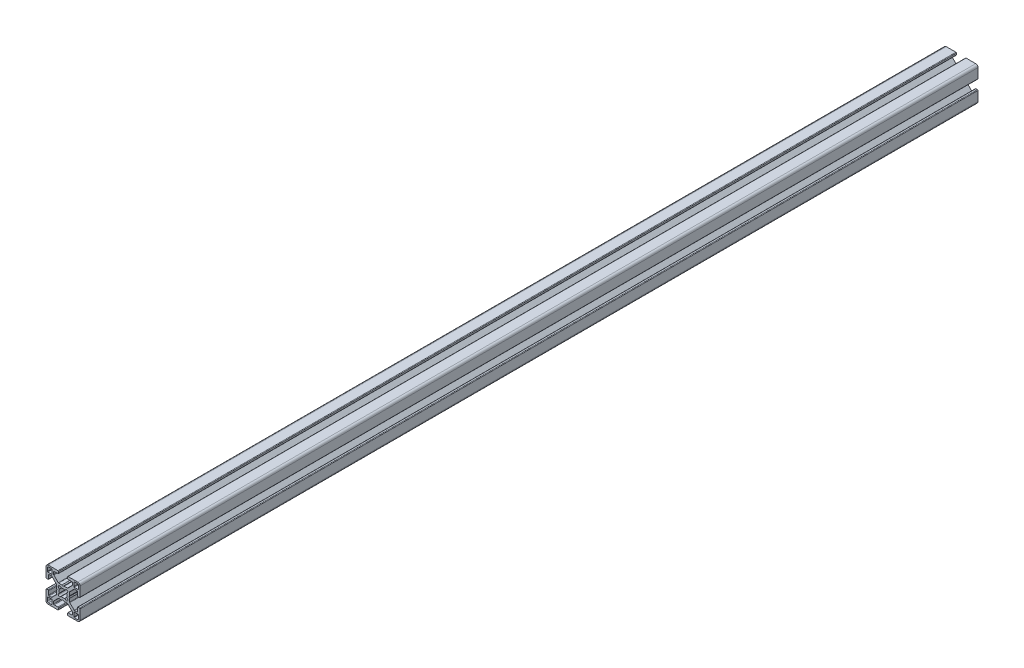
SolidWorks part; units mm, degrees
ref_plane "Plano frontal" through (0, 0, 0) normal (0, 0, 1) x (1, 0, 0)
ref_plane "Plano superior" through (0, 0, 0) normal (0, 1, 0) x (1, 0, 0)
ref_plane "Plano direito" through (0, 0, 0) normal (1, 0, 0) x (0, 0, -1)
ref_plane "Plano1"
sketch "Esboço1" plane through (0, 0, 0) normal (0, 0, 1) x (1, 0, 0)
  line L0 (-13, -15) -> (-4.508, -15)
  line L1 (-4, -14.492) -> (-4, -13.251)
  line L2 (-4.508, -12.743) -> (-7.742, -12.743)
  line L3 (-8.25, -12.235) -> (-8.25, -10.2642)
  line L4 (-8.1012, -9.905) -> (-4.1795, -5.9833)
  line L5 (-3.8203, -5.8345) -> (-0.949, -5.8345)
  line L6 (-0.949, -5.8345) -> (0, -5.325)
  line L7 (0, -5.325) -> (0.949, -5.8345)
  line L8 (0.949, -5.8345) -> (3.8216, -5.8345)
  line L9 (4.1808, -5.9833) -> (8.1012, -9.9037)
  line L10 (8.25, -10.2629) -> (8.25, -12.235)
  line L11 (7.742, -12.743) -> (4.508, -12.743)
  line L12 (4, -13.251) -> (4, -14.492)
  line L13 (4.508, -15) -> (13, -15)
  line L14 (15, -13) -> (15, -4.508)
  line L15 (14.492, -4) -> (13.251, -4)
  line L16 (12.743, -4.508) -> (12.743, -7.742)
  line L17 (12.235, -8.25) -> (10.2642, -8.25)
  line L18 (9.905, -8.1012) -> (5.9833, -4.1795)
  line L19 (5.8345, -3.8203) -> (5.8345, -0.949)
  line L20 (5.8345, -0.949) -> (5.325, 0)
  line L21 (5.325, 0) -> (5.8345, 0.949)
  line L22 (5.8345, 0.949) -> (5.8345, 3.8216)
  line L23 (5.9833, 4.1808) -> (9.9037, 8.1012)
  line L24 (10.2629, 8.25) -> (12.235, 8.25)
  line L25 (12.743, 7.742) -> (12.743, 4.508)
  line L26 (13.251, 4) -> (14.492, 4)
  line L27 (15, 4.508) -> (15, 13)
  line L28 (13, 15) -> (4.508, 15)
  line L29 (4, 14.492) -> (4, 13.251)
  line L30 (4.508, 12.743) -> (7.742, 12.743)
  line L31 (8.25, 12.235) -> (8.25, 10.2642)
  line L32 (8.1012, 9.905) -> (4.1795, 5.9833)
  line L33 (3.8203, 5.8345) -> (0.949, 5.8345)
  line L34 (0.949, 5.8345) -> (0, 5.325)
  line L35 (0, 5.325) -> (-0.949, 5.8345)
  line L36 (-0.949, 5.8345) -> (-3.8216, 5.8345)
  line L37 (-4.1808, 5.9833) -> (-8.1012, 9.9037)
  line L38 (-8.25, 10.2629) -> (-8.25, 12.235)
  line L39 (-7.742, 12.743) -> (-4.508, 12.743)
  line L40 (-4, 13.251) -> (-4, 14.492)
  line L41 (-4.508, 15) -> (-13, 15)
  line L42 (-15, 13) -> (-15, 4.508)
  line L43 (-14.492, 4) -> (-13.251, 4)
  line L44 (-12.743, 4.508) -> (-12.743, 7.742)
  line L45 (-12.235, 8.25) -> (-10.2642, 8.25)
  line L46 (-9.905, 8.1012) -> (-5.9833, 4.1795)
  line L47 (-5.8345, 3.8203) -> (-5.8345, 0.949)
  line L48 (-5.8345, 0.949) -> (-5.325, 0)
  line L49 (-5.325, 0) -> (-5.8345, -0.949)
  line L50 (-5.8345, -0.949) -> (-5.8345, -3.8216)
  line L51 (-5.9833, -4.1808) -> (-9.9037, -8.1012)
  line L52 (-10.2629, -8.25) -> (-12.235, -8.25)
  line L53 (-12.743, -7.742) -> (-12.743, -4.508)
  line L54 (-13.251, -4) -> (-14.492, -4)
  line L55 (-15, -4.508) -> (-15, -13)
  line L56 (9.5, 13.319) -> (9.5, 9.881)
  line L57 (9.881, 9.5) -> (13.319, 9.5)
  line L58 (13.7, 9.881) -> (13.7, 12.7)
  line L59 (12.7, 13.7) -> (9.881, 13.7)
  line L60 (9.5, -9.881) -> (9.5, -13.319)
  line L61 (9.881, -13.7) -> (12.7, -13.7)
  line L62 (13.7, -12.7) -> (13.7, -9.881)
  line L63 (13.319, -9.5) -> (9.881, -9.5)
  line L64 (-13.7, -9.881) -> (-13.7, -12.7)
  line L65 (-12.7, -13.7) -> (-9.881, -13.7)
  line L66 (-9.5, -13.319) -> (-9.5, -9.881)
  line L67 (-9.881, -9.5) -> (-13.319, -9.5)
  line L68 (-13.7, 12.7) -> (-13.7, 9.881)
  line L69 (-13.319, 9.5) -> (-9.881, 9.5)
  line L70 (-9.5, 9.881) -> (-9.5, 13.319)
  line L71 (-9.881, 13.7) -> (-12.7, 13.7)
  line L72 (-4.0107, 2.5139) -> (-3.1982, 1.4942)
  line L73 (-3.1982, -1.4942) -> (-4.0107, -2.5139)
  line L74 (-2.5139, -4.0107) -> (-1.4942, -3.1982)
  line L75 (1.4942, -3.1982) -> (2.5139, -4.0107)
  line L76 (4.0107, -2.5139) -> (3.1982, -1.4942)
  line L77 (3.1982, 1.4942) -> (4.0107, 2.5139)
  line L78 (2.5139, 4.0107) -> (1.4942, 3.1982)
  line L79 (-1.4942, 3.1982) -> (-2.5139, 4.0107)
  arc A0 (-15, -13) -> (-13, -15) centre (-13, -13) ccw
  arc A1 (-4.508, -15) -> (-4, -14.492) centre (-4.508, -14.492) ccw
  arc A2 (-4, -13.251) -> (-4.508, -12.743) centre (-4.508, -13.251) ccw
  arc A3 (-8.25, -12.235) -> (-7.742, -12.743) centre (-7.742, -12.235) ccw
  arc A4 (-8.1012, -9.905) -> (-8.25, -10.2642) centre (-7.742, -10.2642) ccw
  arc A5 (-3.8203, -5.8345) -> (-4.1795, -5.9833) centre (-3.8203, -6.3425) ccw
  arc A6 (4.1808, -5.9833) -> (3.8216, -5.8345) centre (3.8216, -6.3425) ccw
  arc A7 (8.25, -10.2629) -> (8.1012, -9.9037) centre (7.742, -10.2629) ccw
  arc A8 (7.742, -12.743) -> (8.25, -12.235) centre (7.742, -12.235) ccw
  arc A9 (4.508, -12.743) -> (4, -13.251) centre (4.508, -13.251) ccw
  arc A10 (4, -14.492) -> (4.508, -15) centre (4.508, -14.492) ccw
  arc A11 (13, -15) -> (15, -13) centre (13, -13) ccw
  arc A12 (15, -4.508) -> (14.492, -4) centre (14.492, -4.508) ccw
  arc A13 (13.251, -4) -> (12.743, -4.508) centre (13.251, -4.508) ccw
  arc A14 (12.235, -8.25) -> (12.743, -7.742) centre (12.235, -7.742) ccw
  arc A15 (9.905, -8.1012) -> (10.2642, -8.25) centre (10.2642, -7.742) ccw
  arc A16 (5.8345, -3.8203) -> (5.9833, -4.1795) centre (6.3425, -3.8203) ccw
  arc A17 (5.9833, 4.1808) -> (5.8345, 3.8216) centre (6.3425, 3.8216) ccw
  arc A18 (10.2629, 8.25) -> (9.9037, 8.1012) centre (10.2629, 7.742) ccw
  arc A19 (12.743, 7.742) -> (12.235, 8.25) centre (12.235, 7.742) ccw
  arc A20 (12.743, 4.508) -> (13.251, 4) centre (13.251, 4.508) ccw
  arc A21 (14.492, 4) -> (15, 4.508) centre (14.492, 4.508) ccw
  arc A22 (15, 13) -> (13, 15) centre (13, 13) ccw
  arc A23 (4.508, 15) -> (4, 14.492) centre (4.508, 14.492) ccw
  arc A24 (4, 13.251) -> (4.508, 12.743) centre (4.508, 13.251) ccw
  arc A25 (8.25, 12.235) -> (7.742, 12.743) centre (7.742, 12.235) ccw
  arc A26 (8.1012, 9.905) -> (8.25, 10.2642) centre (7.742, 10.2642) ccw
  arc A27 (3.8203, 5.8345) -> (4.1795, 5.9833) centre (3.8203, 6.3425) ccw
  arc A28 (-4.1808, 5.9833) -> (-3.8216, 5.8345) centre (-3.8216, 6.3425) ccw
  arc A29 (-8.25, 10.2629) -> (-8.1012, 9.9037) centre (-7.742, 10.2629) ccw
  arc A30 (-7.742, 12.743) -> (-8.25, 12.235) centre (-7.742, 12.235) ccw
  arc A31 (-4.508, 12.743) -> (-4, 13.251) centre (-4.508, 13.251) ccw
  arc A32 (-4, 14.492) -> (-4.508, 15) centre (-4.508, 14.492) ccw
  arc A33 (-13, 15) -> (-15, 13) centre (-13, 13) ccw
  arc A34 (-15, 4.508) -> (-14.492, 4) centre (-14.492, 4.508) ccw
  arc A35 (-13.251, 4) -> (-12.743, 4.508) centre (-13.251, 4.508) ccw
  arc A36 (-12.235, 8.25) -> (-12.743, 7.742) centre (-12.235, 7.742) ccw
  arc A37 (-9.905, 8.1012) -> (-10.2642, 8.25) centre (-10.2642, 7.742) ccw
  arc A38 (-5.8345, 3.8203) -> (-5.9833, 4.1795) centre (-6.3425, 3.8203) ccw
  arc A39 (-5.9833, -4.1808) -> (-5.8345, -3.8216) centre (-6.3425, -3.8216) ccw
  arc A40 (-10.2629, -8.25) -> (-9.9037, -8.1012) centre (-10.2629, -7.742) ccw
  arc A41 (-12.743, -7.742) -> (-12.235, -8.25) centre (-12.235, -7.742) ccw
  arc A42 (-12.743, -4.508) -> (-13.251, -4) centre (-13.251, -4.508) ccw
  arc A43 (-14.492, -4) -> (-15, -4.508) centre (-14.492, -4.508) ccw
  arc A44 (9.5, 9.881) -> (9.881, 9.5) centre (9.881, 9.881) ccw
  arc A45 (13.319, 9.5) -> (13.7, 9.881) centre (13.319, 9.881) ccw
  arc A46 (13.7, 12.7) -> (12.7, 13.7) centre (12.7, 12.7) ccw
  arc A47 (9.881, 13.7) -> (9.5, 13.319) centre (9.881, 13.319) ccw
  arc A48 (9.5, -13.319) -> (9.881, -13.7) centre (9.881, -13.319) ccw
  arc A49 (12.7, -13.7) -> (13.7, -12.7) centre (12.7, -12.7) ccw
  arc A50 (13.7, -9.881) -> (13.319, -9.5) centre (13.319, -9.881) ccw
  arc A51 (9.881, -9.5) -> (9.5, -9.881) centre (9.881, -9.881) ccw
  arc A52 (-13.7, -12.7) -> (-12.7, -13.7) centre (-12.7, -12.7) ccw
  arc A53 (-9.881, -13.7) -> (-9.5, -13.319) centre (-9.881, -13.319) ccw
  arc A54 (-9.5, -9.881) -> (-9.881, -9.5) centre (-9.881, -9.881) ccw
  arc A55 (-13.319, -9.5) -> (-13.7, -9.881) centre (-13.319, -9.881) ccw
  arc A56 (-13.7, 9.881) -> (-13.319, 9.5) centre (-13.319, 9.881) ccw
  arc A57 (-9.881, 9.5) -> (-9.5, 9.881) centre (-9.881, 9.881) ccw
  arc A58 (-9.5, 13.319) -> (-9.881, 13.7) centre (-9.881, 13.319) ccw
  arc A59 (-12.7, 13.7) -> (-13.7, 12.7) centre (-12.7, 12.7) ccw
  arc A60 (-2.5139, 4.0107) -> (-4.0107, 2.5139) centre (-3.142, 3.142) ccw
  arc A61 (-3.1982, 1.4942) -> (-3.1982, -1.4942) centre (0, 0) ccw
  arc A62 (-4.0107, -2.5139) -> (-2.5139, -4.0107) centre (-3.142, -3.142) ccw
  arc A63 (-1.4942, -3.1982) -> (1.4942, -3.1982) centre (0, 0) ccw
  arc A64 (2.5139, -4.0107) -> (4.0107, -2.5139) centre (3.142, -3.142) ccw
  arc A65 (3.1982, -1.4942) -> (3.1982, 1.4942) centre (0, 0) ccw
  arc A66 (4.0107, 2.5139) -> (2.5139, 4.0107) centre (3.142, 3.142) ccw
  arc A67 (1.4942, 3.1982) -> (-1.4942, 3.1982) centre (0, 0) ccw
extrude "Extrusion1" add sketch "Esboço1" against normal blind 792 contours L54 A43 L55 A0 L0 A1 L1 A2 L2 A3 L3 A4 L4 A5 L5 L6 L7 L8 A6 L9 A7 L10 A8 L11 A9 L12 A10 L13 A11 L14 A12 L15 A13 L16 A14 L17 A15 L18 A16 L19 L20 L21 L22 A17 L23 A18 L24 A19 L25 A20 L26
